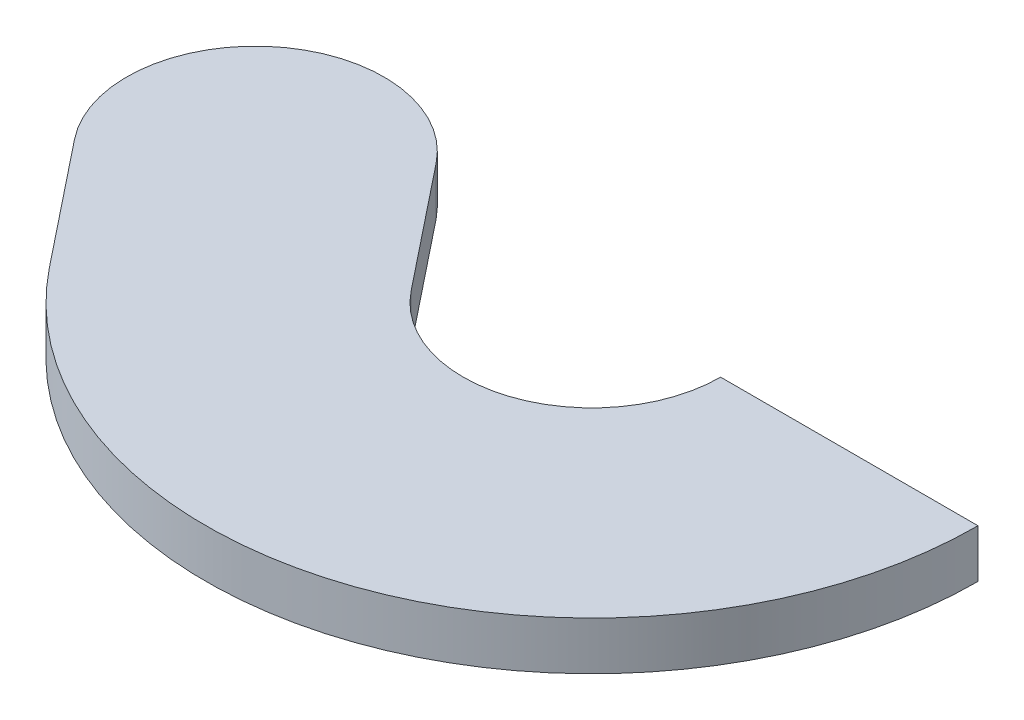
SolidWorks part; units mm, degrees
ref_plane "Front Plane" through (0, 0, 0) normal (0, 0, 1) x (1, 0, 0)
ref_plane "Top Plane" through (0, 0, 0) normal (0, 1, 0) x (1, 0, 0)
ref_plane "Right Plane" through (0, 0, 0) normal (1, 0, 0) x (0, 0, -1)
sketch "Sketch3" plane through (0, 0, 0) normal (0, 1, 0) x (1, 0, 0)
  line L0 (-39.7289, -31.6584) -> (-78.5525, 17.0624)
  line L1 (-119.1868, -94.9751) -> (-158.0103, -46.2544)
  line L2 (50.8, 0) -> (152.4, 0)
  arc A0 (152.4, 0) -> (-119.1868, -94.9751) centre (0, 0) cw
  arc A1 (50.8, 0) -> (-39.7289, -31.6584) centre (0, 0) cw
  arc A2 (-158.0103, -46.2544) -> (-78.5525, 17.0624) centre (-118.2814, -14.596) cw
  dimension "D1" = 50.8
  dimension "D2" = 152.4
extrude "Boss-Extrude1" add sketch "Sketch3" along normal mid plane 19.05
sketch "Sketch4" plane through (0, 0, 0) normal (1, 0, 0) x (0, 0, -1)
  line L0 (-50.8, -9.525) -> (-50.8, 9.525)
split line "Split Line1"
